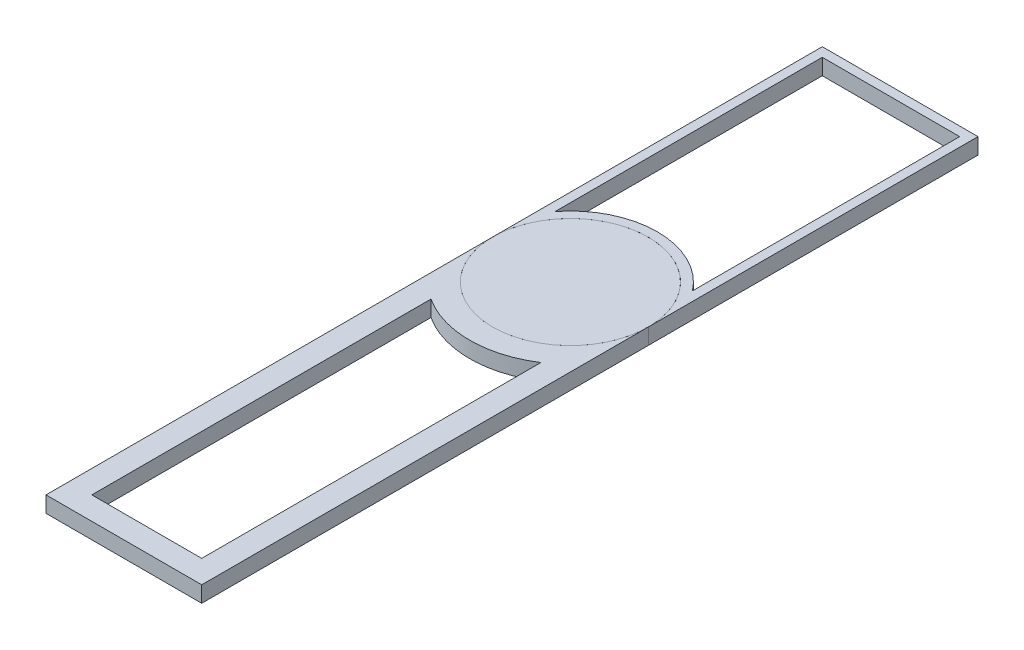
SolidWorks part; units mm, degrees
ref_plane "Front Plane" through (0, 0, 0) normal (0, 0, 1) x (1, 0, 0)
ref_plane "Top Plane" through (0, 0, 0) normal (0, 1, 0) x (1, 0, 0)
ref_plane "Right Plane" through (0, 0, 0) normal (1, 0, 0) x (0, 0, -1)
sketch "Croquis1" plane through (0, 0, 0) normal (0, 1, 0) x (1, 0, 0)
  circle A0 centre (0, 0) radius 17
  dimension "D1" = 34
extrude "Saliente-Extruir1" add sketch "Croquis1" along normal blind 3.5
ref_plane "Plano1" through (0, 0, 27.5) normal (0, 0, 1) x (1, 0, 0)
sketch "Croquis2" plane through (0, 0, 27.5) normal (0, 0, 1) x (1, 0, 0)
  line L2 (17, 3.5) -> (-17, 3.5)
  line L3 (17, 3.5) -> (17, 0)
  line L4 (17, 0) -> (-17, 0)
  line L5 (-17, 3.5) -> (-17, 0)
extrude "Saliente-Extruir2" add sketch "Croquis2" along normal blind 70 and the other way up to next separate body
shell "Vaciado3" thickness 5
ref_plane "Plano2" through (0, 0, -17) normal (0, 0, -1) x (-1, 0, 0)
sketch "Croquis7" plane through (0, 0, -17) normal (0, 0, -1) x (-1, 0, 0)
  line L1 (-17, 0) -> (17, 0)
  line L2 (-17, 0) -> (-17, 3.5)
  line L3 (-17, 3.5) -> (17, 3.5)
  line L4 (17, 0) -> (17, 3.5)
extrude "Saliente-Extruir4" add sketch "Croquis7" along normal blind 55 and the other way up to surface separate body
shell "Vaciado4" thickness 2
equation "\"A\"=60"
